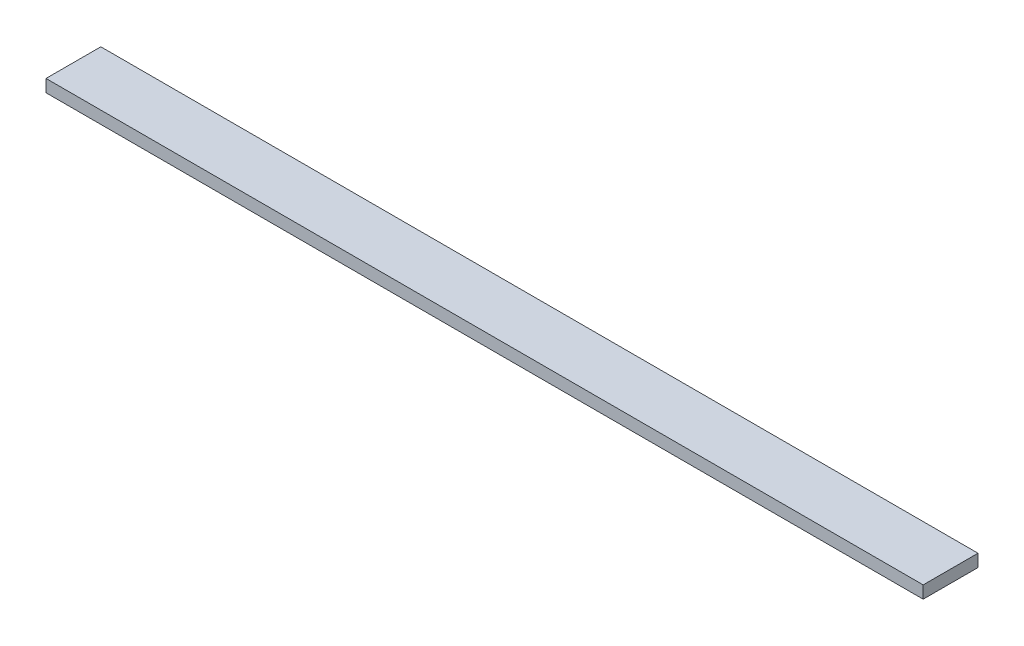
SolidWorks part; units mm, degrees
ref_plane "Front Plane" through (0, 0, 0) normal (0, 0, 1) x (1, 0, 0)
ref_plane "Top Plane" through (0, 0, 0) normal (0, 1, 0) x (1, 0, 0)
ref_plane "Right Plane" through (0, 0, 0) normal (1, 0, 0) x (0, 0, -1)
sketch "Sketch1" plane through (0, 0, 0) normal (0, 1, 0) x (1, 0, 0)
  line L1 (-600, 37.5) -> (600, 37.5)
  line L2 (-600, 37.5) -> (-600, -37.5)
  line L3 (-600, -37.5) -> (600, -37.5)
  line L4 (600, 37.5) -> (600, -37.5)
  line L5 (-600, 37.5) -> (600, -37.5) construction
  line L6 (-600, -37.5) -> (600, 37.5) construction
  point P0 (0, 0)
extrude "Boss-Extrude1" add sketch "Sketch1" along normal blind 17
